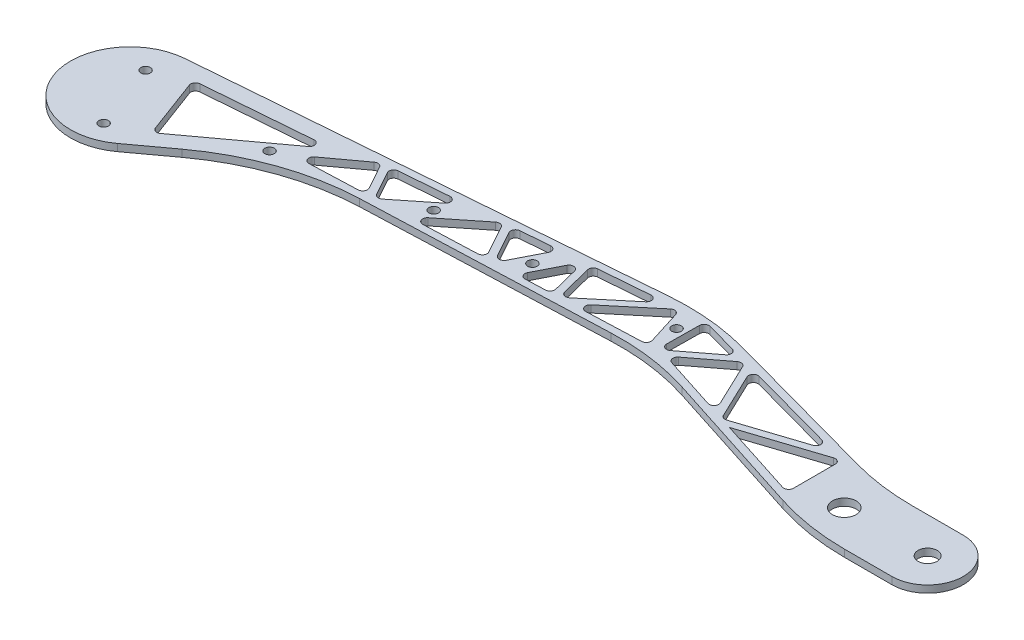
SolidWorks part; units mm, degrees
ref_plane "Front Plane" through (0, 0, 0) normal (0, 0, 1) x (1, 0, 0)
ref_plane "Top Plane" through (0, 0, 0) normal (0, 1, 0) x (1, 0, 0)
ref_plane "Right Plane" through (0, 0, 0) normal (1, 0, 0) x (0, 0, -1)
sketch "Sketch1" plane through (0, 0, 0) normal (0, 1, 0) x (1, 0, 0)
  line L0 (0, 0) -> (-300, 0) construction
  line L1 (0, 0) -> (35, 0) construction
  line L2 (0, 15) -> (35, 15)
  line L3 (0, -15) -> (35, -15)
  line L4 (-302.0128, 24.9188) -> (-285.1961, -20.1456) construction
  line L5 (-96.4179, 41.5254) -> (-717.946, -8.6774)
  line L6 (0, 15) -> (-657.0371, 195.7568)
  line L7 (0, 15) -> (-8.2094, -12.5541) construction
  line L8 (-717.946, -8.6774) -> (-94.8534, 15.2636)
  line L9 (-657.0371, 195.7568) -> (-8.2094, -12.5541)
  line L10 (-285.1961, -20.1456) -> (-244.8534, 9.5002)
  line L11 (-8.2094, -12.5541) -> (0, -15)
  circle A0 centre (0, 0) radius 5
  circle A1 centre (-300, 0) radius 25
  circle A2 centre (35, 0) radius 4
  circle A3 centre (0, 0) radius 15
  circle A4 centre (35, 0) radius 15
  point P17 (-244.8534, 9.5002)
  point P20 (-285.1961, -20.1456)
  point P21 (-285.1961, -20.1456)
  point P22 (-285.1961, -20.1456)
  dimension "D1" = 10
  dimension "D4" = 8
  dimension "D5" = 50
  dimension "D6" = 30
  dimension "D7" = 160
  dimension "D2" = 300
  dimension "D3" = 35
  dimension "D8" = 160
  dimension "D9" = 100
  dimension "D10" = 150
  dimension "D11" = 91
extrude "Boss-Extrude1" add sketch "Sketch1" along normal blind 3 contours L8 A1 | A1 L8 | A1 L8 L9 L5 | A1 L10 L8 | A3 L6 L5 L9 | A3 A0 | A4 L2 A3 L3 | A4 A2
fillet "Fillet1" radius 100 5 edges at (0, 1.5, -15) (-96.4179, 1.5, -41.5254) (-94.8534, 1.5, -15.2636) (-244.8534, 1.5, -9.5002) (0, 1.5, 15)
sketch "Sketch2" plane through (0, 3, 0) normal (0, 1, 0) x (1, 0, 0)
  line L0 (-285.1961, -20.1456) -> (-302.0128, 24.9188) construction
  line L1 (-292.2159, 18.6874) -> (-281.8765, -9.0194)
  line L2 (-281.8765, -9.0194) -> (-238.2394, 23.0472)
  line L3 (-238.2394, 23.0472) -> (-292.2159, 18.6874)
  line L4 (-285.1961, -20.1456) -> (-269.5743, -8.666) construction
  line L5 (-113.9933, 40.1058) -> (-302.0128, 24.9188) construction
  line L6 (-17.7547, 16.773) -> (-17.7547, -6.3387)
  line L7 (-17.7547, -6.3387) -> (-53.3654, 5.0944)
  line L8 (-53.3654, 5.0944) -> (-17.7547, 16.773)
  line L9 (-22.99, 18.2133) -> (-69.8958, 31.1175)
  line L10 (-69.8958, 31.1175) -> (-58.2301, 6.6562)
  line L11 (-58.2301, 6.6562) -> (-22.99, 18.2133)
  line L12 (-62.1547, 7.9163) -> (-73.7214, 32.17)
  line L13 (-73.7214, 32.17) -> (-92.6229, 17.6983)
  line L14 (-92.6229, 17.6983) -> (-62.1547, 7.9163)
  line L15 (-13.0208, 18.5821) -> (-79.4168, 36.8483) construction
  line L16 (-78.0647, 9.8735) -> (-15.5008, -10.2131) construction
  line L17 (-86.3511, 35.6445) -> (-12.0577, 15.2057) construction
  line L18 (-62.1547, 7.9163) -> (-53.3654, 5.0944) construction
  line L19 (-77.3519, 33.1687) -> (-96.9203, 18.1864)
  line L20 (-96.9203, 18.1864) -> (-244.1063, 12.5311) construction
  line L21 (-244.1063, 12.5311) -> (-222.6175, 28.3221)
  line L22 (-222.6175, 28.3221) -> (-96.7036, 38.4926) construction
  line L23 (-96.7036, 38.4926) -> (-77.3519, 33.1687)
  line L24 (-214.1981, 10.678) -> (-112.4731, 14.5866) construction
  line L25 (-96.7036, 38.4926) -> (-96.9203, 18.1864)
  line L26 (-106.5555, 37.6968) -> (-100.4103, 18.0523)
  line L27 (-100.4103, 18.0523) -> (-131.5203, 16.857)
  line L28 (-131.5203, 16.857) -> (-106.5555, 37.6968)
  line L29 (-111.7384, 37.2782) -> (-136.4276, 16.6684)
  line L30 (-136.4276, 16.6684) -> (-141.0342, 34.9118)
  line L31 (-141.0342, 34.9118) -> (-111.7384, 37.2782)
  line L32 (-144.0665, 34.6669) -> (-139.492, 16.5507)
  line L33 (-139.492, 16.5507) -> (-153.57, 16.0097)
  line L34 (-153.57, 16.0097) -> (-144.0665, 34.6669)
  line L35 (-153.4298, 33.9106) -> (-162.7272, 15.6579)
  line L36 (-162.7272, 15.6579) -> (-172.0207, 32.409)
  line L37 (-172.0207, 32.409) -> (-153.4298, 33.9106)
  line L38 (-175.3044, 32.1437) -> (-166.0864, 15.5288)
  line L39 (-166.0864, 15.5288) -> (-197.6515, 14.316)
  line L40 (-197.6515, 14.316) -> (-175.3044, 32.1437)
  line L41 (-222.6175, 28.3221) -> (-214.488, 13.6691)
  line L42 (-214.488, 13.6691) -> (-244.1063, 12.5311)
  line L43 (-219.3339, 28.5873) -> (-211.1288, 13.7982)
  line L44 (-211.1288, 13.7982) -> (-189.5777, 30.9908)
  line L45 (-189.5777, 30.9908) -> (-219.3339, 28.5873)
  line L46 (-194.4361, 21.9981) -> (-196.9306, 25.125) construction
  line L47 (-154.3314, 23.3279) -> (-150.7671, 21.5123) construction
  line L48 (-305.8804, 12.4012) -> (-295.3918, -15.7056) construction
  line L49 (-250.479, 9.0891) -> (-252.8476, 12.3124) construction
  circle A0 centre (-100.4103, 29.9667) radius 2
  circle A1 centre (-154.3314, 23.3279) radius 2
  circle A2 centre (-194.4361, 21.9981) radius 2
  circle A3 centre (-250.479, 9.0891) radius 2
  circle A4 centre (-305.8804, 12.4012) radius 2
  circle A5 centre (-295.3918, -15.7056) radius 2
  dimension "D14" = 4
  dimension "D25" = 4
  dimension "D1" = 7
  dimension "D2" = 7
  dimension "D3" = 7
  dimension "D4" = 3
  dimension "D5" = 3
  dimension "D6" = 3
  dimension "D7" = 3
  dimension "D8" = 32
  dimension "D9" = 3
  dimension "D10" = 3
  dimension "D11" = 3
  dimension "D12" = 3
  dimension "D13" = 5
  dimension "D15" = 3
  dimension "D16" = 3
  dimension "D17" = 3
  dimension "D18" = 3
  dimension "D19" = 8
  dimension "D20" = 8
  dimension "D21" = 4
  dimension "D22" = 4
  dimension "D23" = 8
  dimension "D24" = 30
extrude "Cut-Extrude1" cut sketch "Sketch2" against normal blind 3
fillet "Fillet2" radius 2 35 edges at (-17.7547, 1.5, 6.3387) (-17.7547, 1.5, -16.773) (-22.99, 1.5, -18.2133) (-58.2301, 1.5, -6.6562) (-69.8958, 1.5, -31.1175) (-62.1547, 1.5, -7.9163) (-92.6229, 1.5, -17.6983) (-73.7214, 1.5, -32.17) (-77.3519, 1.5, -33.1687) (-96.9203, 1.5, -18.1864) (-96.7036, 1.5, -38.4926) (-106.5555, 1.5, -37.6968) (-131.5203, 1.5, -16.857) (-100.4103, 1.5, -18.0523) (-141.0342, 1.5, -34.9118) (-136.4276, 1.5, -16.6684) (-111.7384, 1.5, -37.2782) (-153.57, 1.5, -16.0097) (-139.492, 1.5, -16.5507) (-144.0665, 1.5, -34.6669) (-172.0207, 1.5, -32.409) (-162.7272, 1.5, -15.6579) (-153.4298, 1.5, -33.9106) (-189.5777, 1.5, -30.9908) (-219.3339, 1.5, -28.5873) (-211.1288, 1.5, -13.7982) (-197.6515, 1.5, -14.316) (-175.3044, 1.5, -32.1437) (-166.0864, 1.5, -15.5288) (-214.488, 1.5, -13.6691) (-244.1063, 1.5, -12.5311) (-222.6175, 1.5, -28.3221) (-281.8765, 1.5, 9.0194) (-292.2159, 1.5, -18.6874) (-238.2394, 1.5, -23.0472)
